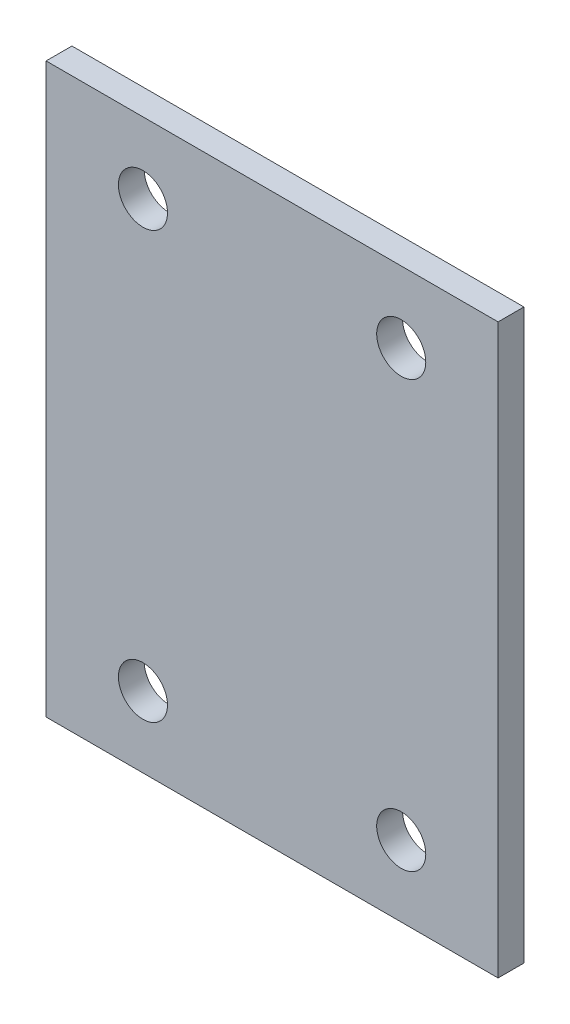
SolidWorks part; units mm, degrees
ref_plane "Спереди" through (0, 0, 0) normal (0, 0, 1) x (1, 0, 0)
ref_plane "Сверху" through (0, 0, 0) normal (0, 1, 0) x (1, 0, 0)
ref_plane "Справа" through (0, 0, 0) normal (1, 0, 0) x (0, 0, -1)
sketch "Эскиз1" plane through (0, 0, 0) normal (0, 0, 1) x (1, 0, 0)
  line L0 (175, -220) -> (175, 220)
  line L1 (175, 220) -> (-175, 220)
  line L2 (-175, 220) -> (-175, -220)
  line L3 (-175, -220) -> (175, -220)
  circle A4 centre (-100, 165) radius 19
  circle A5 centre (100, 165) radius 19
  circle A6 centre (100, -165) radius 19
  circle A7 centre (-100, -165) radius 19
extrude "Бобышка-Вытянуть1" add sketch "Эскиз1" along normal blind 20
